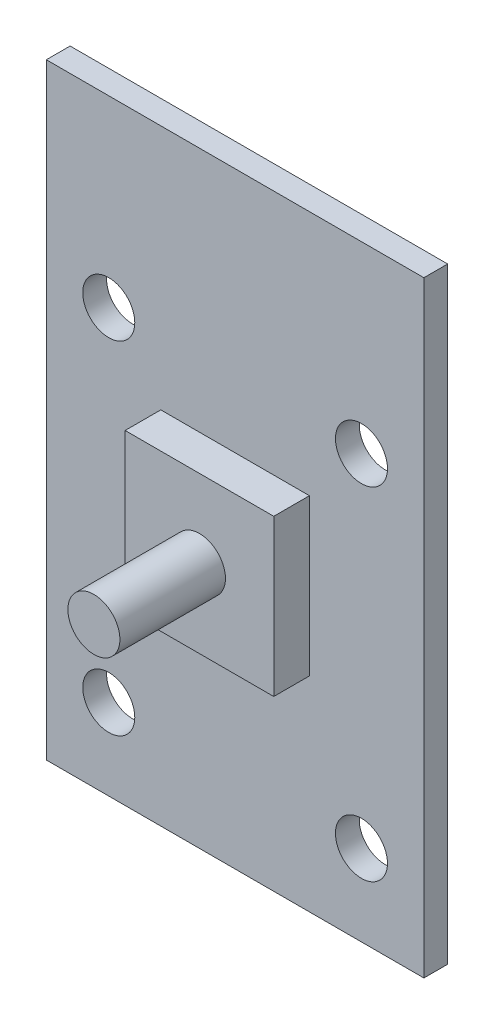
SolidWorks part; units mm, degrees
ref_plane "Plan de face" through (0, 0, 0) normal (0, 0, 1) x (1, 0, 0)
ref_plane "Plan de dessus" through (0, 0, 0) normal (0, 1, 0) x (1, 0, 0)
ref_plane "Plan de droite" through (0, 0, 0) normal (1, 0, 0) x (0, 0, -1)
sketch "Esquisse1" plane through (0, 0, 0) normal (0, 0, 1) x (1, 0, 0)
  line L0 (45.7554, 25.4792) -> (62.7554, 25.4792) construction
  line L1 (41.5554, 60.8247) -> (66.9554, 60.8247)
  line L2 (41.5554, 60.8247) -> (41.5554, 20.0247)
  line L3 (41.5554, 20.0247) -> (66.9554, 20.0247)
  line L4 (66.9554, 60.8247) -> (66.9554, 20.0247)
  line L5 (54.2554, 20.0247) -> (54.2554, 60.8247) construction
  line L6 (62.7554, 25.4792) -> (62.7554, 48.4792) construction
  line L7 (62.7554, 48.4792) -> (45.7554, 48.4792) construction
  line L8 (41.5554, 39.0247) -> (66.9554, 39.0247) construction
  circle A0 centre (62.7554, 25.4792) radius 1.75
  circle A1 centre (45.7554, 25.4792) radius 1.75
  circle A2 centre (62.7554, 48.4792) radius 1.75
  circle A3 centre (45.7554, 48.4792) radius 1.75
  circle A4 centre (54.2554, 39.0247) radius 1.8161
  dimension "D4" = 3.5
  dimension "D6" = 3.5
  dimension "D1" = 25.4
  dimension "D2" = 40.8
  dimension "D3" = 17
  dimension "D5" = 23
  dimension "D7" = 19
extrude "Boss.-Extru.1" add sketch "Esquisse1" along normal blind 1.6
sketch "Esquisse2" plane through (0, 0, 1.6) normal (0, 0, 1) x (1, 0, 0)
  line L1 (49.2554, 44.2747) -> (59.2554, 44.2747)
  line L2 (49.2554, 44.2747) -> (49.2554, 33.7747)
  line L3 (49.2554, 33.7747) -> (59.2554, 33.7747)
  line L4 (59.2554, 44.2747) -> (59.2554, 33.7747)
  line L5 (49.2554, 44.2747) -> (59.2554, 33.7747) construction
  line L6 (49.2554, 33.7747) -> (59.2554, 44.2747) construction
  point P0 (54.2554, 39.0247)
  dimension "D1" = 10
  dimension "D2" = 10.5
extrude "Boss.-Extru.2" add sketch "Esquisse2" along normal blind 2.4
sketch "Esquisse3" plane through (0, 0, 4) normal (0, 0, 1) x (1, 0, 0)
  line L0 (49.2554, 44.2747) -> (59.2554, 33.7747) construction
  circle A0 centre (54.2554, 39.0247) radius 1.75
  dimension "D1" = 3.5
extrude "Boss.-Extru.3" add sketch "Esquisse3" along normal blind 7.1
